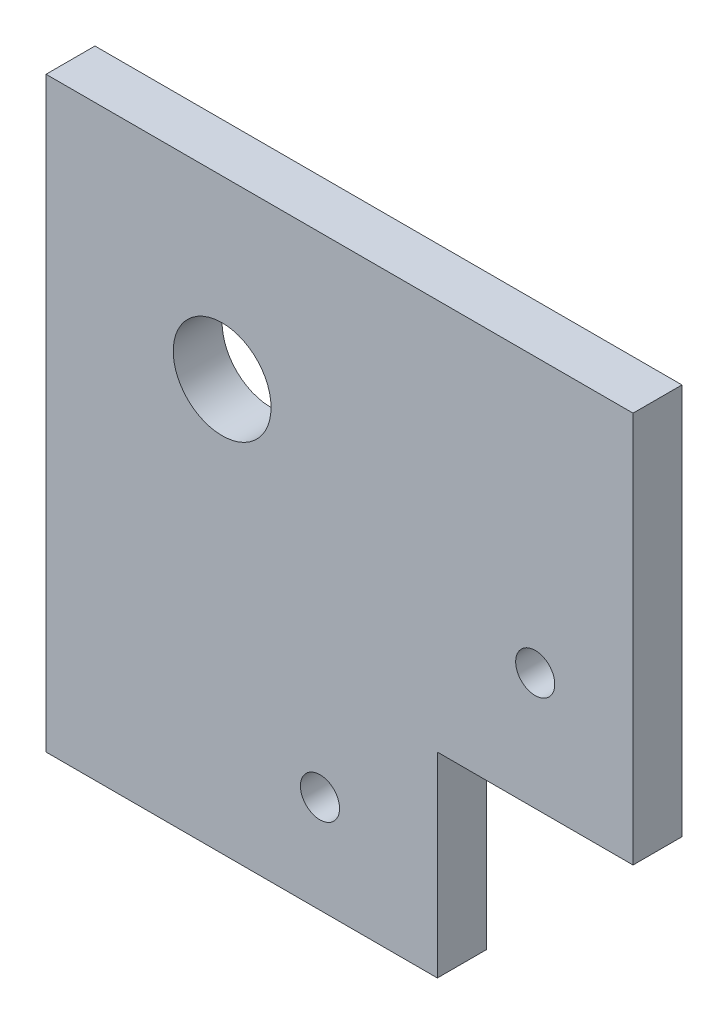
SolidWorks part; units mm, degrees
ref_plane "Płaszczyzna przednia" through (0, 0, 0) normal (0, 0, 1) x (1, 0, 0)
ref_plane "Płaszczyzna górna" through (0, 0, 0) normal (0, 1, 0) x (1, 0, 0)
ref_plane "Płaszczyzna prawa" through (0, 0, 0) normal (1, 0, 0) x (0, 0, -1)
sketch "Sketch1" plane through (0, 0, 0) normal (0, 0, 1) x (1, 0, 0)
  line L1 (0, 0) -> (40, 0)
  line L2 (0, 0) -> (0, 60)
  line L3 (0, 60) -> (60, 60)
  line L4 (60, 20) -> (60, 60)
  line L5 (0, 0) -> (60, 60) construction
  line L6 (0, 60) -> (60, 0) construction
  line L9 (60, 20) -> (40, 20)
  line L10 (40, 0) -> (40, 20)
  line L11 (60, 0) -> (40, 20) construction
  line L12 (60, 20) -> (40, 0) construction
  circle A0 centre (18, 42) radius 5
  point P4 (30, 30)
  point P9 (50, 10)
  dimension "D5" = 10
  dimension "D6" = 42
  dimension "D7" = 42
  dimension "D1" = 60
  dimension "D2" = 60
  dimension "D3" = 20
  dimension "D4" = 20
extrude "Boss-Extrude1" add sketch "Sketch1" along normal blind 5
sketch "Sketch2" plane through (0, 0, 0) normal (0, 0, -1) x (-1, 0, 0)
  line L0 (-40, 20) -> (-60, 20) construction
  line L1 (-60, 20) -> (-60, 60) construction
  line L2 (0, 0) -> (-40, 0) construction
  line L3 (-40, 0) -> (-40, 20) construction
  circle A0 centre (-50, 32) radius 2
  circle A1 centre (-28, 10) radius 2
  dimension "D1" = 4
  dimension "D2" = 12
  dimension "D3" = 10
  dimension "D4" = 4
  dimension "D5" = 10
  dimension "D6" = 12
extrude "Cut-Extrude1" cut sketch "Sketch2" against normal through all
